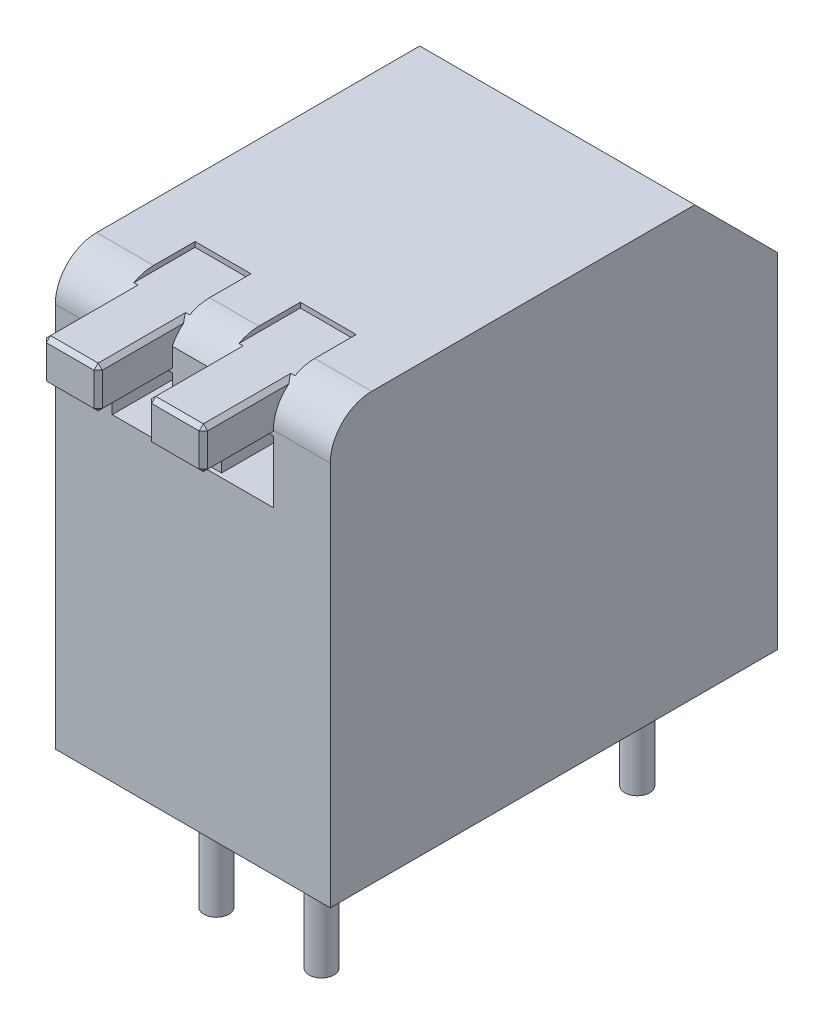
SolidWorks part; units mm, degrees
ref_plane "Спереди" through (0, 0, 0) normal (0, 0, 1) x (1, 0, 0)
ref_plane "Сверху" through (0, 0, 0) normal (0, 1, 0) x (1, 0, 0)
ref_plane "Справа" through (0, 0, 0) normal (1, 0, 0) x (0, 0, -1)
sketch "Эскиз1" plane through (0, 0, 0) normal (1, 0, 0) x (0, 0, -1)
  line L0 (0, 0) -> (-5.4, 0) construction
  line L1 (-5.4, 5.15) -> (5.4, 5.15)
  line L2 (-5.4, 5.15) -> (-5.4, -5.15)
  line L3 (-5.4, -5.15) -> (5.4, -5.15)
  line L4 (5.4, 5.15) -> (5.4, -5.15)
  line L5 (0, 0) -> (0, -5.15) construction
  dimension "D1" = 10.8
  dimension "D2" = 10.3
extrude "Вытянуть1" add sketch "Эскиз1" along normal blind 6.64
chamfer "Фаска1" distance 2 angle 45 1 edges at (3.32, 5.15, -5.4)
sketch "Эскиз2" plane through (0, -5.15, 0) normal (0, -1, 0) x (1, 0, 0)
  line L0 (0, 3.56) -> (6.64, 3.56) construction
  line L1 (0, 5.4) -> (0, -5.4) construction
  line L2 (6.64, 5.4) -> (6.64, -5.4) construction
  line L3 (2.05, 5.4) -> (2.05, -5.4) construction
  line L4 (6.64, 5.4) -> (0, 5.4) construction
  line L5 (6.64, -5.4) -> (0, -5.4) construction
  line L6 (4.59, 5.4) -> (4.59, -5.4) construction
  line L7 (0, -4.06) -> (6.64, -4.06) construction
  circle A0 centre (2.05, 3.56) radius 0.3
  circle A1 centre (4.59, 3.56) radius 0.3
  circle A2 centre (2.05, -4.06) radius 0.3
  circle A3 centre (4.59, -4.06) radius 0.3
  dimension "D5" = 0.6
  dimension "D1" = 7.62
  dimension "D2" = 1.84
  dimension "D3" = 2.05
  dimension "D4" = 2.05
  dimension "D6" = 2.54
extrude "Вытянуть2" add sketch "Эскиз2" along normal blind 3.2
fillet "Скругление1" radius 1 1 edges at (3.32, 5.15, 5.4)
sketch "Эскиз3" plane through (0, 0, 5.4) normal (0, 0, 1) x (1, 0, 0)
  line L0 (0, 2.5295) -> (6.64, 2.5295) construction
  line L2 (6.64, 4.15) -> (6.64, -5.15) construction
  line L3 (0, 5.15) -> (6.64, 5.15) construction
  line L4 (1.375, 5.15) -> (2.725, 5.15)
  line L5 (6.64, 4.15) -> (6.64, 5.15) construction
  line L6 (2.05, -8.35) -> (2.05, 5.15) construction
  line L7 (1.75, -8.35) -> (2.35, -8.35) construction
  line L8 (4.59, -8.35) -> (4.59, 5.15) construction
  line L9 (4.29, -8.35) -> (4.89, -8.35) construction
  line L10 (0, 5.15) -> (6.64, 5.15) construction
  line L11 (3.915, 5.15) -> (5.265, 5.15)
  line L12 (3.915, 5.15) -> (3.915, 2.5295)
  line L13 (3.915, 2.5295) -> (5.265, 2.5295)
  line L14 (5.265, 5.15) -> (5.265, 2.5295)
  line L15 (1.375, 5.15) -> (1.375, 2.5295)
  line L16 (1.375, 2.5295) -> (2.725, 2.5295)
  line L17 (2.725, 5.15) -> (2.725, 2.5295)
  dimension "D1" = 1.35
extrude "Вырез-Вытянуть1" cut sketch "Эскиз3" against normal blind 2
sketch "Эскиз4" plane through (0, 0, 5.4) normal (0, 0, 1) x (1, 0, 0)
  line L1 (1.375, 5.15) -> (5.265, 5.15)
  line L2 (1.375, 5.15) -> (1.375, 2.5295)
  line L3 (1.375, 2.5295) -> (5.265, 2.5295)
  line L4 (5.265, 5.15) -> (5.265, 2.5295)
extrude "Вырез-Вытянуть2" cut sketch "Эскиз4" against normal blind 0.1
sketch "Эскиз5" plane through (0, 0, 3.4) normal (0, 0, 1) x (1, 0, 0)
  line L0 (1.375, 4.15) -> (1.375, 5.15) construction
  line L1 (1.375, 5.0283) -> (2.725, 5.0283)
  line L2 (1.375, 5.0283) -> (1.375, 4.0283)
  line L3 (1.375, 4.0283) -> (2.725, 4.0283)
  line L4 (2.725, 5.0283) -> (2.725, 4.0283)
  line L5 (2.725, 2.5295) -> (2.725, 5.15) construction
  line L6 (1.375, 4.5283) -> (5.265, 4.5283) construction
  line L7 (3.915, 5.0283) -> (5.265, 5.0283)
  line L8 (3.915, 5.0283) -> (3.915, 4.0283)
  line L9 (3.915, 4.0283) -> (5.265, 4.0283)
  line L10 (5.265, 5.0283) -> (5.265, 4.0283)
  line L11 (3.915, 4.5859) -> (3.915, 5.15) construction
  line L12 (5.265, 2.5295) -> (5.265, 5.15) construction
  dimension "D1" = 1
extrude "Вытянуть3" add sketch "Эскиз5" along normal blind 3.69
chamfer "Фаска2" distance 0.1 angle 45 16 edges at (2.05, 5.0283, 7.09) (2.725, 4.5283, 7.09) (2.05, 4.0283, 7.09) (1.375, 4.5283, 7.09) (2.725, 5.0283, 5.984) (2.725, 4.0283, 6.195) (1.375, 4.0283, 6.245) (1.375, 5.0283, 5.984) (4.59, 5.0283, 7.09) (5.265, 5.0283, 5.984) (5.265, 4.5283, 7.09) (5.265, 4.0283, 6.245) (4.59, 4.0283, 7.09) (3.915, 4.0283, 6.195) (3.915, 4.5283, 7.09) (3.915, 5.0283, 5.984)
